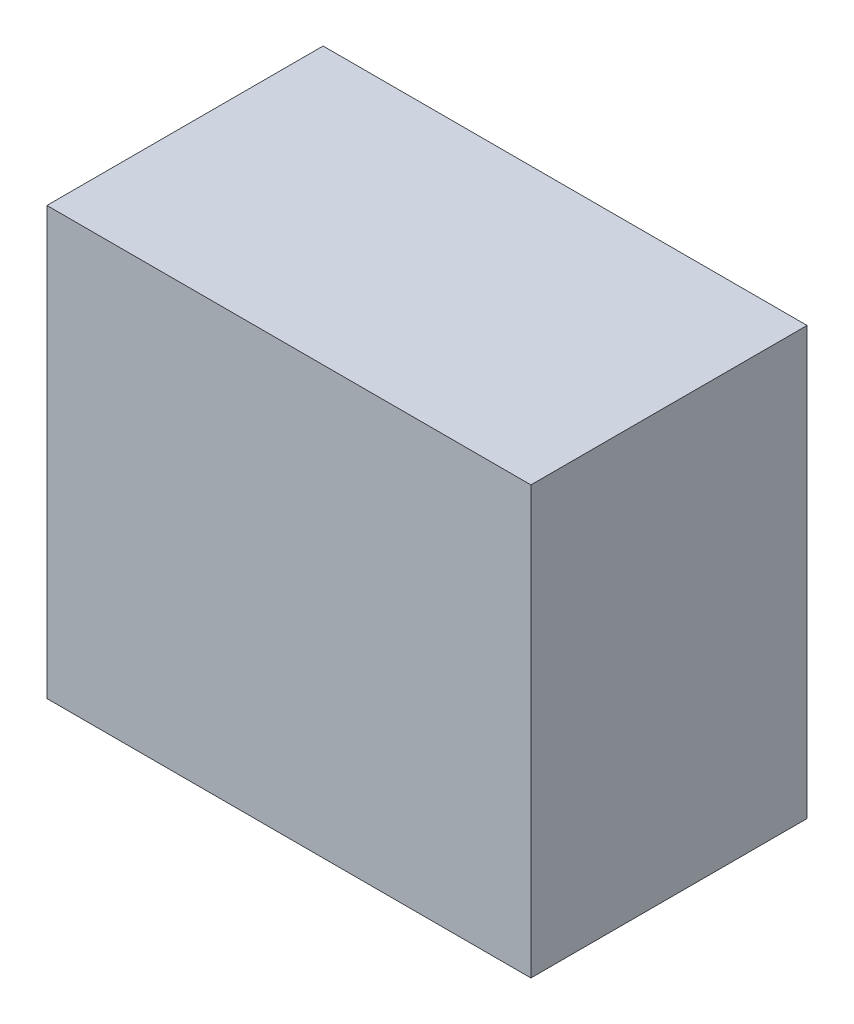
SolidWorks part; units mm, degrees
ref_plane "Front Plane" through (0, 0, 0) normal (0, 0, 1) x (1, 0, 0)
ref_plane "Top Plane" through (0, 0, 0) normal (0, 1, 0) x (1, 0, 0)
ref_plane "Right Plane" through (0, 0, 0) normal (1, 0, 0) x (0, 0, -1)
sketch "Sketch1" plane through (0, 0, 0) normal (0, 1, 0) x (1, 0, 0)
  line L1 (-85, 48.5) -> (85, 48.5)
  line L2 (-85, 48.5) -> (-85, -48.5)
  line L3 (-85, -48.5) -> (85, -48.5)
  line L4 (85, 48.5) -> (85, -48.5)
  dimension "D1" = 170
  dimension "D2" = 85
  dimension "D3" = 97
  dimension "D4" = 48.5
extrude "Boss-Extrude1" add sketch "Sketch1" along normal blind 150
